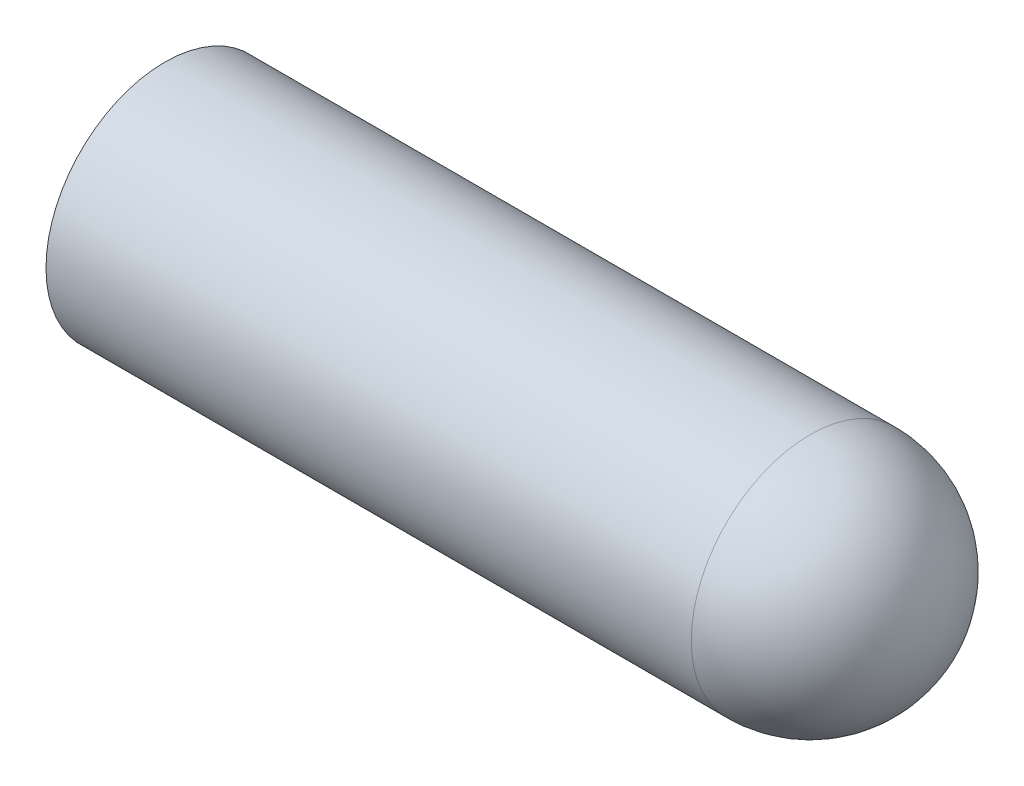
SolidWorks part; units mm, degrees
ref_plane "Alzado" through (0, 0, 0) normal (0, 0, 1) x (1, 0, 0)
ref_plane "Planta" through (0, 0, 0) normal (0, 1, 0) x (1, 0, 0)
ref_plane "Vista lateral" through (0, 0, 0) normal (1, 0, 0) x (0, 0, -1)
sketch "Croquis2" plane through (0, 0, 0) normal (0, 0, 1) x (1, 0, 0)
  line L0 (0, 0) -> (38, 0)
  line L1 (0, 0) -> (0, 7)
  line L2 (0, 7) -> (38, 7)
  line L4 (38, 0) -> (45, 0)
  arc A0 (45, 0) -> (38, 7) centre (38, 0) ccw
  dimension "D1" = 45
  dimension "D2" = 7
revolve "Revolución1" add sketch "Croquis2" angle 360 about L0
sketch "Croquis3" plane through (0, 0, 0) normal (-1, 0, 0) x (0, 0, 1)
  circle A0 centre (0, 0) radius 1.6
  dimension "D1" = 3.2
extrude "Cortar-Extruir1" cut sketch "Croquis3" against normal blind 6 contours A0
